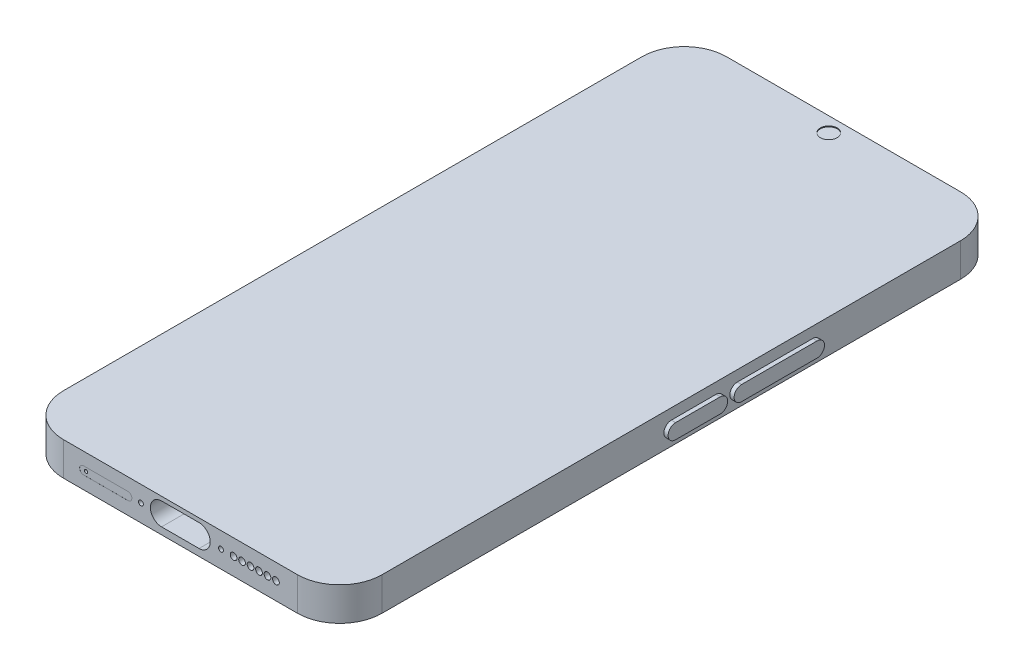
SolidWorks part; units mm, degrees
ref_plane "前视基准面" through (0, 0, 0) normal (0, 0, 1) x (1, 0, 0)
ref_plane "上视基准面" through (0, 0, 0) normal (0, 1, 0) x (1, 0, 0)
ref_plane "右视基准面" through (0, 0, 0) normal (1, 0, 0) x (0, 0, -1)
other "Configuration Table"
sketch "草图1" plane through (0, 0, 0) normal (0, 1, 0) x (1, 0, 0)
  line L1 (-37.65, -78.35) -> (37.65, -78.35)
  line L2 (-37.65, -78.35) -> (-37.65, 78.35)
  line L3 (-37.65, 78.35) -> (37.65, 78.35)
  line L4 (37.65, -78.35) -> (37.65, 78.35)
  line L5 (-37.65, -78.35) -> (37.65, 78.35) construction
  line L6 (-37.65, 78.35) -> (37.65, -78.35) construction
  point P0 (0, 0)
  dimension "D1" = 156.7
  dimension "D2" = 75.3
extrude "凸台-拉伸1" add sketch "草图1" along normal blind 7.9
fillet "圆角1" radius 10 4 edges at (37.65, 3.95, -78.35) (-37.65, 3.95, -78.35) (-37.65, 3.95, 78.35) (37.65, 3.95, 78.35)
sketch "草图3" plane through (0, 7.9, 0) normal (0, 1, 0) x (1, 0, 0)
  circle A0 centre (0, 74.8526) radius 2
extrude "切除-拉伸1" cut sketch "草图3" against normal blind 0.2
sketch "草图6" plane through (0, 0, 78.35) normal (0, 0, 1) x (1, 0, 0)
  line L0 (-22.8819, 3.9782) -> (-12.412, 3.9782) construction
  line L1 (-22.8819, 4.91) -> (-12.412, 4.91)
  line L2 (-22.8819, 3.0464) -> (-12.412, 3.0464)
  arc A0 (-22.8819, 4.91) -> (-22.8819, 3.0464) centre (-22.8819, 3.9782) ccw
  arc A1 (-12.412, 3.0464) -> (-12.412, 4.91) centre (-12.412, 3.9782) ccw
  point P2 (-17.6469, 3.9782)
  dimension "D1" = 10.4699
extrude "切除-拉伸2" cut sketch "草图6" against normal blind 0.01
sketch "草图9" plane through (0, 0, 78.34) normal (0, 0, 1) x (1, 0, 0)
  circle A0 centre (-22.3183, 4.0345) radius 0.3997
extrude "切除-拉伸3" cut sketch "草图9" against normal blind 0.6
sketch "草图12" plane through (0, 0, 78.35) normal (0, 0, 1) x (1, 0, 0)
  line L0 (-4.4524, 4.2863) -> (4.396, 4.2863) construction
  line L1 (-4.4524, 6.9352) -> (4.396, 6.9352)
  line L2 (-4.4524, 1.6374) -> (4.396, 1.6374)
  arc A0 (-4.4524, 6.9352) -> (-4.4524, 1.6374) centre (-4.4524, 4.2863) ccw
  arc A1 (4.396, 1.6374) -> (4.396, 6.9352) centre (4.396, 4.2863) ccw
  point P2 (-0.0282, 4.2863)
extrude "切除-拉伸4" cut sketch "草图12" against normal blind 20.6
sketch "草图13" plane through (0, 0, 78.35) normal (0, 0, 1) x (1, 0, 0)
  circle A0 centre (-9.3469, 4.0863) radius 0.5781
  circle A1 centre (9.5836, 4.0863) radius 0.5781
extrude "切除-拉伸5" cut sketch "草图13" against normal blind 20.6
sketch "草图14" plane through (0, 0, 78.35) normal (0, 0, 1) x (1, 0, 0)
  line L0 (-27.65, 0) -> (27.65, 0) construction
  circle A0 centre (11.9482, 4.0863) radius 0.75
  circle A1 centre (13.9482, 4.0863) radius 0.75
  circle A2 centre (15.9482, 4.0863) radius 0.75
  circle A3 centre (17.9482, 4.0863) radius 0.75
  circle A4 centre (19.9482, 4.0863) radius 0.75
  circle A5 centre (21.9482, 4.0863) radius 0.75
  dimension "D2" = 4.0863
  dimension "D3" = 1.5
  dimension "D1" = 6
sketch "草图15" plane through (0, 0, 78.35) normal (0, 0, 1) x (1, 0, 0)
  line L0 (12.5681, 4.1018) -> (14.5681, 4.1018) construction
  circle A0 centre (12.5681, 4.1018) radius 0.7963
  circle A1 centre (14.5681, 4.1018) radius 0.7963
  circle A2 centre (16.5681, 4.1018) radius 0.7963
  circle A3 centre (18.5681, 4.1018) radius 0.7963
  circle A4 centre (20.5681, 4.1018) radius 0.7963
  circle A5 centre (22.5681, 4.1018) radius 0.7963
  dimension "D3" = 1.5925
  dimension "D2" = 2
  dimension "D1" = 6
extrude "切除-拉伸6" cut sketch "草图15" against normal blind 20.6
sketch "草图16" plane through (0, 0, -78.35) normal (0, 0, -1) x (-1, 0, 0)
  line L0 (-16.054, 4.056) -> (-11.054, 4.056) construction
  circle A0 centre (-16.054, 4.056) radius 0.8242
  circle A1 centre (-11.054, 4.056) radius 0.8242
  dimension "D1" = 2
  dimension "D2" = 5
extrude "切除-拉伸8" cut sketch "草图16" against normal blind 5.6
sketch "草图17" plane through (37.65, 0, 0) normal (1, 0, 0) x (0, 0, -1)
  line L0 (15.5988, 3.5905) -> (33.4322, 3.5905) construction
  line L1 (15.5988, 5.3497) -> (33.4322, 5.3497)
  line L2 (15.5988, 1.8312) -> (33.4322, 1.8312)
  line L3 (0, 3.5905) -> (10.5556, 3.5905) construction
  line L4 (0, 5.3497) -> (10.5556, 5.3497)
  line L5 (0, 1.8312) -> (10.5556, 1.8312)
  arc A0 (15.5988, 5.3497) -> (15.5988, 1.8312) centre (15.5988, 3.5905) ccw
  arc A1 (33.4322, 1.8312) -> (33.4322, 5.3497) centre (33.4322, 3.5905) ccw
  arc A2 (0, 5.3497) -> (0, 1.8312) centre (0, 3.5905) ccw
  arc A3 (10.5556, 1.8312) -> (10.5556, 5.3497) centre (10.5556, 3.5905) ccw
  point P2 (24.5155, 3.5905)
  point P9 (5.2778, 3.5905)
  dimension "D3" = 1.7593
  dimension "D1" = 17.8334
  dimension "D2" = 10.5556
  dimension "D4" = 1.7593
extrude "凸台-拉伸2" add sketch "草图17" along normal blind 1
sketch "草图19" plane through (0, 0, 0) normal (0, -1, 0) x (1, 0, 0)
  line L0 (-37.65, 52.7434) -> (37.65, 52.7434) construction
  line L1 (-37.65, -68.35) -> (-37.65, 68.35) construction
  line L2 (37.65, 68.35) -> (37.65, -68.35) construction
  text T0 "MEIZU" font "SWGDT" height 3.5
extrude "切除-拉伸9" cut sketch "草图19" against normal blind 0.03
